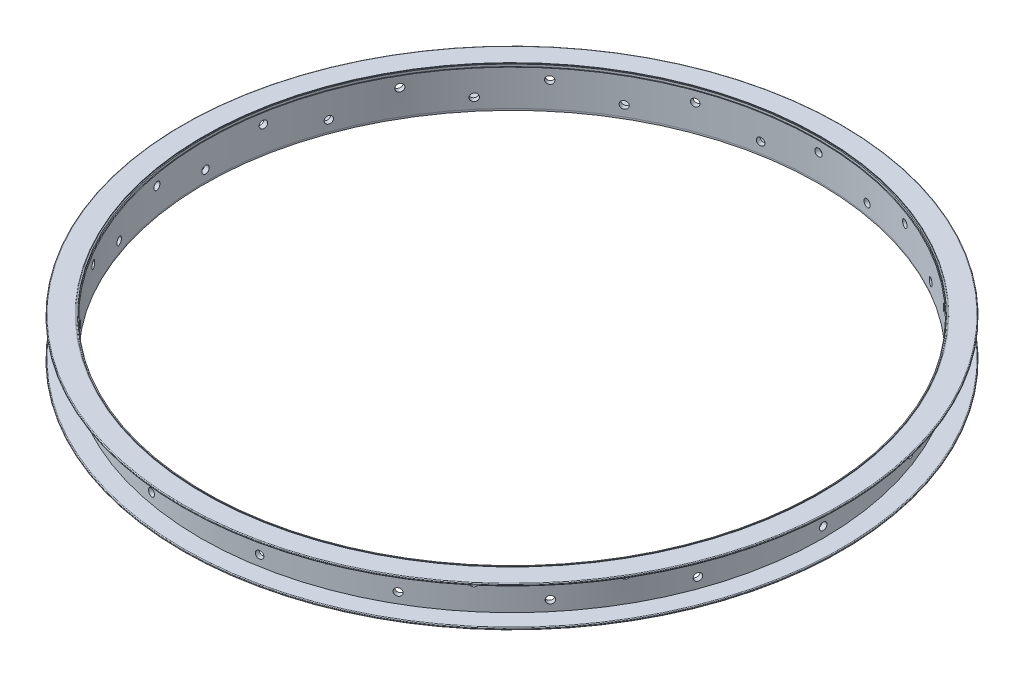
SolidWorks part; units mm, degrees
material "7075-O (SS)"
ref_plane "Front Plane" through (0, 0, 0) normal (0, 0, 1) x (1, 0, 0)
ref_plane "Top Plane" through (0, 0, 0) normal (0, 1, 0) x (1, 0, 0)
ref_plane "Right Plane" through (0, 0, 0) normal (1, 0, 0) x (0, 0, -1)
sketch "Sketch1" plane through (0, 0, 0) normal (1, 0, 0) x (0, 0, -1)
  line L0 (0, 0) -> (240, 0) construction
  line L1 (0, 0) -> (0, 26.1717) construction
  line L2 (206.4373, -13.5) -> (207.0352, -13.5)
  line L3 (220.9373, -12) -> (209.0946, -12)
  line L4 (221.4373, -12.5) -> (221.4373, -13)
  line L5 (209.0946, -12) -> (220.9373, -12)
  line L6 (207.0352, 13.5) -> (207.0352, 13)
  line L7 (207.0352, 13) -> (207.5352, 13)
  line L8 (207.5352, 13) -> (207.5352, 13.5)
  line L9 (207.5352, -13) -> (207.5352, -13.5)
  line L10 (207.0352, -13) -> (207.5352, -13)
  line L11 (207.0352, -13.5) -> (207.0352, -13)
  line L12 (207.5352, 13.5) -> (220.9373, 13.5)
  line L13 (209.0946, 12) -> (220.9373, 12)
  line L14 (221.4373, 12.5) -> (221.4373, 13)
  line L15 (220.9373, 12) -> (209.0946, 12)
  line L16 (209.0946, 12) -> (209.0946, -12)
  line L17 (207.5352, -13.5) -> (220.9373, -13.5)
  line L18 (205.9373, -12) -> (205.9373, 12)
  line L19 (205.9373, 12) -> (206.4373, 12)
  line L20 (206.4373, -13.5) -> (206.4373, -12)
  line L21 (206.4373, 13.5) -> (207.0352, 13.5)
  line L22 (205.9373, -12) -> (206.4373, -12)
  line L23 (206.4373, 12) -> (206.4373, 13.5)
  arc A0 (221.4373, 13) -> (220.9373, 13.5) centre (220.9373, 13) ccw
  arc A1 (221.4373, 12.5) -> (220.9373, 12) centre (220.9373, 12.5) cw
  arc A2 (221.4373, -12.5) -> (220.9373, -12) centre (220.9373, -12.5) ccw
  arc A3 (221.4373, -13) -> (220.9373, -13.5) centre (220.9373, -13) cw
  point P5 (221.4373, 13.5)
  dimension "D2" = 0.5
  dimension "D1" = 240
  dimension "D3" = 15
  dimension "D4" = 0.5
  dimension "D5" = 0.5
  dimension "D6" = 24
  dimension "D7" = 0.5
revolve "Revolve2" add sketch "Sketch1" angle 360 about L1
ref_plane "Plane2" through (0, 0, 209.0946) normal (0, 0, 1) x (1, 0, 0)
sketch "Sketch3" plane through (0, 0, 209.0946) normal (0, 0, 1) x (1, 0, 0)
  circle A0 centre (0, 5) radius 2.5
  dimension "D2" = 5
extrude "Cut-Extrude1" cut sketch "Sketch3" against normal up to next
pattern_circular "CirPattern1" count 18 over 360 about axis through (0, 13.5, 0) along (0, -1, 0) of "Cut-Extrude1"
ref_plane "Plane3" through (209.0946, 0, 0) normal (1, 0, 0) x (0, 0, -1)
sketch "Sketch4" plane through (209.0946, 0, 0) normal (1, 0, 0) x (0, 0, -1)
  circle A0 centre (0, -5) radius 2.5
  dimension "D2" = 5
extrude "Cut-Extrude2" cut sketch "Sketch4" against normal up to next
pattern_circular "CirPattern2" count 18 over 360 about axis through (0, 13.5, 0) along (0, -1, 0) of "Cut-Extrude2"
